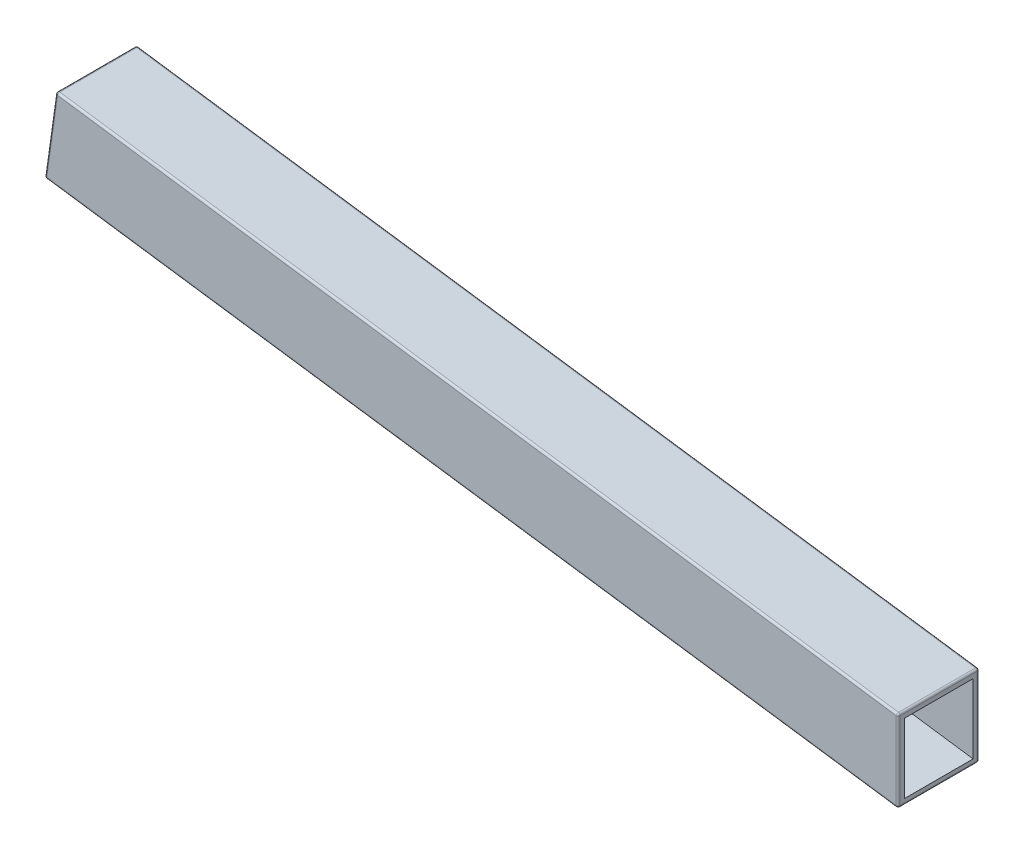
SolidWorks part; units mm, degrees
ref_plane "Front Plane" through (0, 0, 0) normal (0, 0, 1) x (1, 0, 0)
ref_plane "Top Plane" through (0, 0, 0) normal (0, 1, 0) x (1, 0, 0)
ref_plane "Right Plane" through (0, 0, 0) normal (1, 0, 0) x (0, 0, -1)
sketch "Sketch1" plane through (0, 0, 0) normal (0, 0, 1) x (1, 0, 0)
  line L0 (119.9742, 0) -> (-143.6311, 0) construction
  line L1 (0, 0) -> (-421.4795, 59.2351)
  line L2 (-421.4795, 59.2351) -> (-415.9126, 98.8458)
  line L3 (-415.9126, 98.8458) -> (0, 40.3931)
  line L4 (0, 40.3931) -> (0, 0)
  dimension "D1" = 8
  dimension "D2" = 40
  dimension "D3" = 420
extrude "Boss-Extrude1" add sketch "Sketch1" along normal blind 40
sketch "Sketch2" plane through (-421.4795, 59.2351, 0) normal (-0.9903, 0.1392, 0) x (0, 0, 1)
  line L0 (3, 37) -> (37, 37)
  line L1 (37, 37) -> (37, 3)
  line L2 (37, 3) -> (3, 3)
  line L3 (3, 3) -> (3, 37)
  line L4 (40, 40) -> (0, 40) construction
  line L5 (0, 40) -> (0, 0) construction
  line L6 (40, 40) -> (40, 0) construction
  line L7 (40, 0) -> (0, 0) construction
  dimension "D1" = 3
  dimension "D2" = 3
  dimension "D3" = 3
  dimension "D4" = 3
extrude "Cut-Extrude1" cut sketch "Sketch2" against normal through all
fillet "Fillet1" radius 1 12 edges at (-421.4795, 59.2351, 20) (0, 0, 20) (-418.6961, 79.0404, 0) (-210.7398, 29.6175, 0) (0, 20.1966, 0) (0, 40.3931, 20) (-415.9126, 98.8458, 20) (-207.9563, 69.6195, 0) (-210.7398, 29.6175, 40) (-418.6961, 79.0404, 40) (-207.9563, 69.6195, 40) (0, 20.1966, 40)
